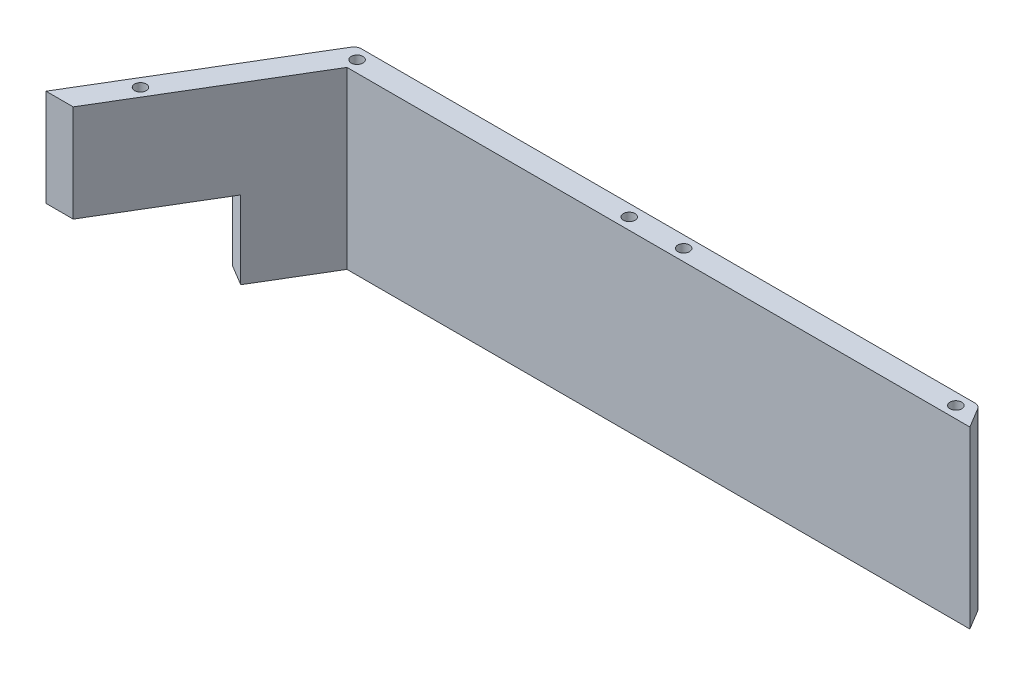
SolidWorks part; units mm, degrees
ref_plane "Front Plane" through (0, 0, 0) normal (0, 0, 1) x (1, 0, 0)
ref_plane "Top Plane" through (0, 0, 0) normal (0, 1, 0) x (1, 0, 0)
ref_plane "Right Plane" through (0, 0, 0) normal (1, 0, 0) x (0, 0, -1)
sketch "Sketch1" plane through (0, 0, 0) normal (0, 1, 0) x (1, 0, 0)
  line L0 (-110, 0) -> (-80, 50)
  line L1 (-80, 50) -> (80, 50)
  line L3 (76.6, 44) -> (-76.6, 44)
  line L4 (-76.6, 44) -> (-103, 0)
  line L5 (-103, 0) -> (-110, 0)
  line L6 (0, -55) -> (0, 55) construction
  line L7 (103, 0) -> (110, 0)
  line L8 (76.6, 44) -> (103, 0)
  line L9 (110, 0) -> (80, 50)
  dimension "D1" = 6
  dimension "D2" = 7
  dimension "D3" = 50
  dimension "D4" = 30
extrude "Boss-Extrude1" add sketch "Sketch1" along normal mid plane 45
sketch "Sketch2" plane through (0, 22.5, 0) normal (0, 1, 0) x (1, 0, 0)
  line L1 (-80, 50) -> (-110, 0) construction
  line L2 (80, 50) -> (-80, 50) construction
  line L3 (0, -55) -> (0, 55) construction
  circle A0 centre (-98.7014, 13) radius 1.5
  circle A1 centre (-77, 47) radius 1.5
  circle A2 centre (-7, 47) radius 1.5
  circle A3 centre (7, 47) radius 1.5
  circle A4 centre (77, 47) radius 1.5
  circle A5 centre (98.7014, 13) radius 1.5
  dimension "D2" = 3
  dimension "D3" = 3
  dimension "D5" = 3
  dimension "D1" = 70
  dimension "D4" = 7
  dimension "D6" = 3
  dimension "D7" = 3
  dimension "D8" = 3
  dimension "D9" = 37
extrude "Cut-Extrude1" cut sketch "Sketch2" against normal blind 5
fillet "Fillet1" radius 2 2 edges at (80, 0, -50) (-80, 0, -50)
sketch "Sketch3" plane through (-80.8824, 0, -48.5294) normal (-0.8575, 0, -0.5145) x (-0.5145, 0, 0.8575)
  line L0 (56.5945, -22.5) -> (56.5945, -2.5)
  line L1 (56.5945, -22.5) -> (21.5945, -22.5)
  line L3 (56.5945, -2.5) -> (21.5945, -2.5)
  line L4 (21.5945, -22.5) -> (21.5945, -2.5)
  line L5 (-0.5826, 22.5) -> (56.5945, 22.5) construction
  line L6 (56.5945, 22.5) -> (56.5945, -22.5) construction
  dimension "D1" = 25
  dimension "D2" = 35
  dimension "D3" = 20
  dimension "D4" = 0
extrude "Cut-Extrude2" cut sketch "Sketch3" against normal blind 10
sketch "Sketch6" plane through (0, 0, 0) normal (1, 0, 0) x (0, 0, -1)
  line L0 (0, -22.5) -> (49.029, -22.5) construction
  line L1 (0, 22.5) -> (44, 22.5)
  line L2 (0, 22.5) -> (0, -22.5)
  line L3 (0, -22.5) -> (44, -22.5)
  line L4 (44, 22.5) -> (44, -22.5)
  line L5 (50, 22.5) -> (50, -22.5) construction
  dimension "D1" = 6
extrude "Cut-Extrude3" cut sketch "Sketch6" along normal through all
